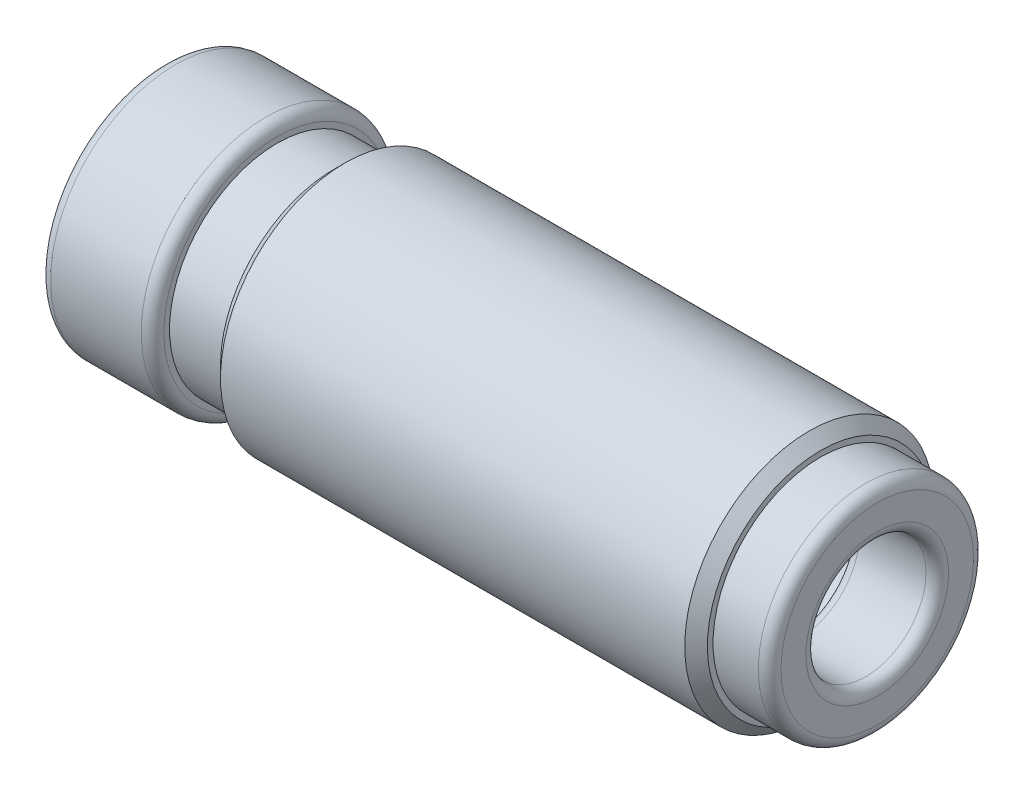
SolidWorks part; units mm, degrees
ref_plane "Plano frontal" through (0, 0, 0) normal (0, 0, 1) x (1, 0, 0)
ref_plane "Plano superior" through (0, 0, 0) normal (0, 1, 0) x (1, 0, 0)
ref_plane "Plano direito" through (0, 0, 0) normal (1, 0, 0) x (0, 0, -1)
sketch "Esboço1" plane through (0, 0, 0) normal (0, 0, 1) x (1, 0, 0)
  line L0 (0, 0) -> (0, 11)
  line L1 (0, 11) -> (10, 11)
  line L2 (10, 11) -> (10.0016, 9.5)
  line L3 (10.0016, 9.5) -> (15.0016, 9.5)
  line L4 (15.0016, 9.5) -> (15.0016, 11)
  line L5 (15.0016, 11) -> (58, 11)
  line L8 (63, 9.5) -> (63, 0)
  line L9 (63, 0) -> (0, 0)
  line L10 (58, 11) -> (58, 9.5)
  line L15 (58, 9.5) -> (63, 9.5)
  point P11 (5, 11)
  point P12 (36.5008, 11)
  dimension "D1" = 11
  dimension "D2" = 10
  dimension "D3" = 5
  dimension "D4" = 63
  dimension "D5" = 5
  dimension "D6" = 1.5
  dimension "D7" = 1.5
revolve "Revolução1" add sketch "Esboço1" angle 360 about L9
cosmetic thread "Representação de rosca1" parameters "D1"=43, "D2"=19.252
hole_wizard "Furo roscado de M14x1.51" positions "Esboço2" profile "Esboço3" tap size "M14x1.5" standard "DIN"
sketch "Esboço2" plane through (0, 0, 0) normal (-1, 0, 0) x (0, 0, 1)
  point P0 (0, 0)
sketch "Esboço3" plane through (0, 0, 0) normal (0, 1, 0) x (0, 0, 1)
  line L0 (0, 0) -> (0, 58.7554)
  line L1 (0, 58.7554) -> (6.25, 55)
  line L2 (6.25, 55) -> (6.25, 0.775)
  line L3 (6.25, 0.775) -> (7.025, 0)
  line L5 (7.025, 0) -> (0, 0)
  line L6 (-6.25, 0.775) -> (-7.025, 0) construction
  line L10 (0, 58.7554) -> (-6.25, 55) construction
  line L11 (0, -6.35) -> (0, 107.95) construction
  dimension "Tap Drill Dia." = 12.5
  dimension "Tap Drill Depth" = 55
  dimension "Near C'Sink Dia." = 14.05
  dimension "Near C'Sink Angle" = 90
  dimension "Drill Angle" = 118
cosmetic thread "Rosca de furo1" parameters "D1"=55, "D2"=14
hole_wizard "Furo1" positions "Esboço4" profile "Esboço5" legacy
sketch "Esboço4" plane through (63, 0, 0) normal (1, 0, 0) x (0, 0, -1)
  point P0 (0, 0)
sketch "Esboço5" plane through (63, 0, 0) normal (0, 1, 0) x (0, 0, -1)
  line L0 (0, 0) -> (0, 8)
  line L1 (0, 8) -> (5.3, 8)
  line L2 (5.3, 8) -> (5.3, 0)
  line L3 (5.3, 0) -> (0, 0)
  line L4 (0, 110) -> (0, -10) construction
  dimension "Diameter" = 10.6
  dimension "Depth" = 8
fillet "Filete1" radius 1 5 edges at (55.5708, 0, 5.3) (0, 11, 0) (10, 11, 0) (63, 9.5, 0) (63, 0, -5.3)
chamfer "Chanfro1" distance 1 angle 45 2 edges at (15.0016, 11, 0) (58, 11, 0)
